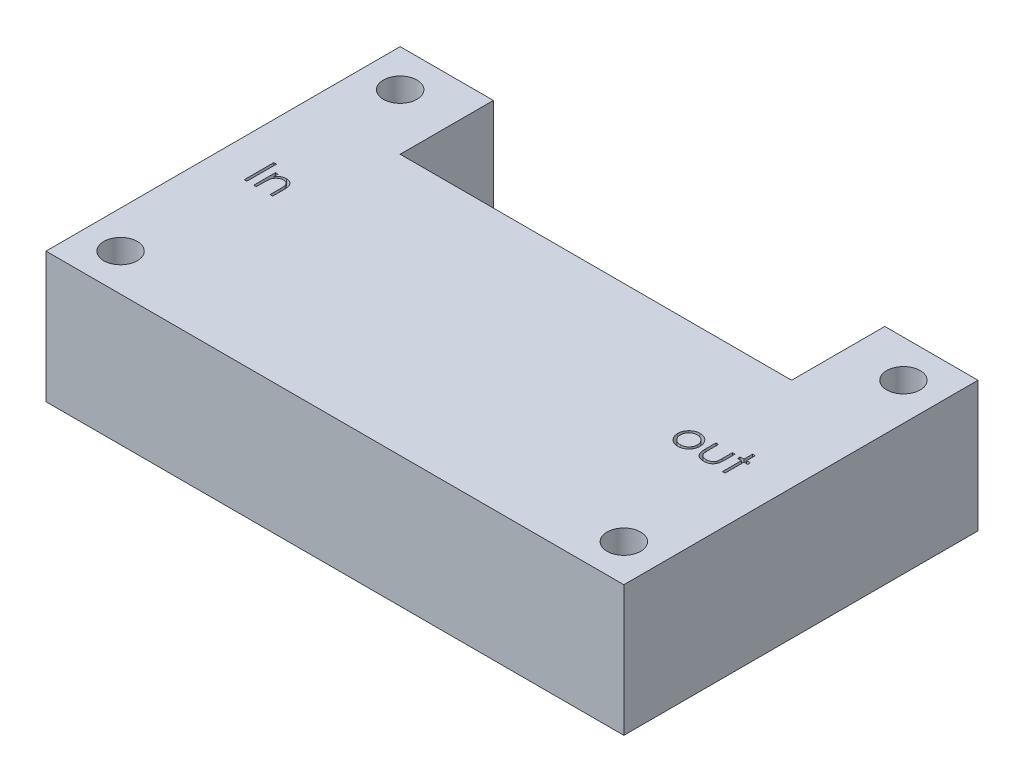
SolidWorks part; units mm, degrees
ref_plane "Plan de face" through (0, 0, 0) normal (0, 0, 1) x (1, 0, 0)
ref_plane "Plan de dessus" through (0, 0, 0) normal (0, 1, 0) x (1, 0, 0)
ref_plane "Plan de droite" through (0, 0, 0) normal (1, 0, 0) x (0, 0, -1)
sketch "Esquisse1" plane through (0, 0, 0) normal (0, 1, 0) x (1, 0, 0)
  line L1 (-31, -19) -> (31, -19)
  line L2 (-31, -19) -> (-31, 19)
  line L3 (-31, 19) -> (31, 19)
  line L4 (31, -19) -> (31, 19)
  line L5 (-31, -19) -> (31, 19) construction
  line L6 (-31, 19) -> (31, -19) construction
  point P0 (0, 0)
  dimension "D1" = 62
  dimension "D2" = 38
extrude "Boss.-Extru.1" add sketch "Esquisse1" along normal blind 14
sketch "Esquisse2" plane through (0, 14, 0) normal (0, 1, 0) x (1, 0, 0)
  line L0 (31, 19) -> (-31, 19) construction
  line L1 (-21, 19) -> (21, 19)
  line L2 (-21, 19) -> (-21, 9)
  line L3 (-21, 9) -> (21, 9)
  line L4 (21, 19) -> (21, 9)
  line L5 (-31, 19) -> (-31, -19) construction
  line L6 (31, -19) -> (31, 19) construction
  dimension "D1" = 10
  dimension "D2" = 10
  dimension "D3" = 10
extrude "Enlèv. mat.-Extru.1" cut sketch "Esquisse2" against normal up to surface (14 mm away) up to face at (0, 0, 0)
hole_wizard "Dégagement M31" positions "Esquisse3" profile "Esquisse4" hole size "M3" standard "Ansi Metric" end condition through all
sketch "Esquisse3" plane through (0, 14, 0) normal (0, 1, 0) x (1, 0, 0)
  line L5 (-27, 15) -> (27, -15) construction
  line L7 (27, 15) -> (-27, -15) construction
  line L9 (-31, 19) -> (-31, -19) construction
  line L10 (-21, 9) -> (21, 9) construction
  point P0 (-27, 15)
  point P2 (27, 15)
  point P4 (27, -15)
  point P6 (-27, -15)
  point P41 (-31, 0)
  point P42 (0, 0)
  point P45 (0, 9)
  dimension "D1" = 54
  dimension "D2" = 30
sketch "Esquisse4" plane through (-27, 14, -15) normal (1, 0, 0) x (0, 0, 1)
  line L0 (0, 0) -> (0, 14)
  line L1 (0, 14) -> (1.8, 14)
  line L2 (1.8, 14) -> (1.8, 0)
  line L5 (1.8, 0) -> (0, 0)
  line L11 (0, -6.35) -> (0, 107.95) construction
  dimension "Diamètre du perçage jusqu'au prochain" = 3.6
  dimension "Profondeur du perçage jusqu'au prochain" = 14
sketch "Esquisse5" plane through (0, 14, 0) normal (0, 1, 0) x (1, 0, 0)
  text T0 "In"
  text T1 "out"
extrude "Enlèv. mat.-Extru.2" cut sketch "Esquisse5" against normal blind 12
